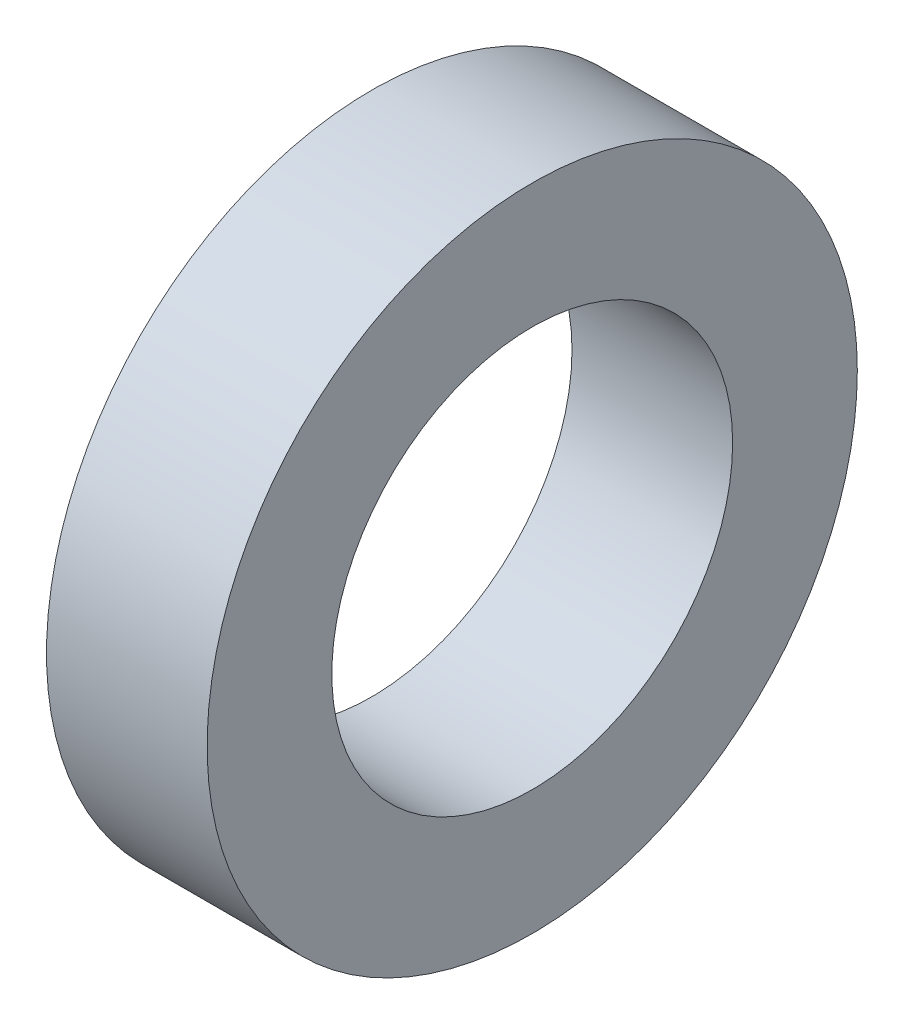
SolidWorks part; units mm, degrees
material "PLA"
ref_plane "Front Plane" through (0, 0, 0) normal (0, 0, 1) x (1, 0, 0)
ref_plane "Top Plane" through (0, 0, 0) normal (0, 1, 0) x (1, 0, 0)
ref_plane "Right Plane" through (0, 0, 0) normal (1, 0, 0) x (0, 0, -1)
sketch "Sketch1" plane through (0, 0, 0) normal (1, 0, 0) x (0, 0, -1)
  circle A0 centre (0, 0) radius 3.3274
  circle A1 centre (0, 0) radius 5.3975
  dimension "D1" = 6.6548
  dimension "D2" = 10.795
extrude "Boss-Extrude1" add sketch "Sketch1" along normal blind 2.667
